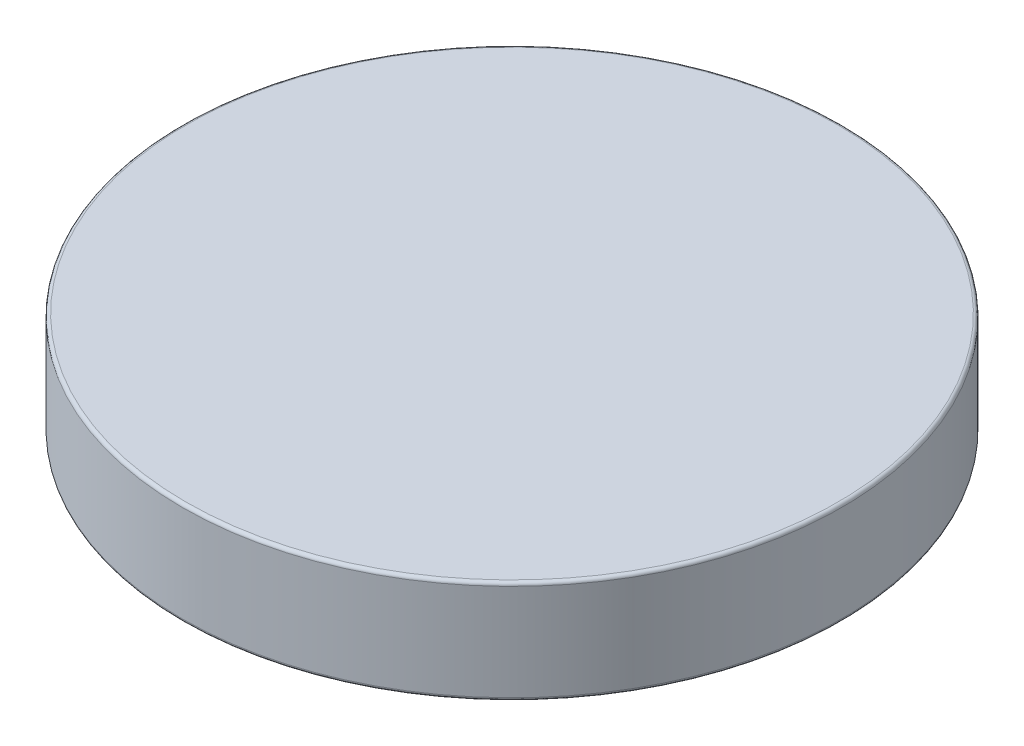
SolidWorks part; units mm, degrees
ref_plane "Front Plane" through (0, 0, 0) normal (0, 0, 1) x (1, 0, 0)
ref_plane "Top Plane" through (0, 0, 0) normal (0, 1, 0) x (1, 0, 0)
ref_plane "Right Plane" through (0, 0, 0) normal (1, 0, 0) x (0, 0, -1)
sketch "Sketch1" plane through (0, 0, 0) normal (0, 1, 0) x (1, 0, 0)
  circle A0 centre (0, 0) radius 2.54
  dimension "D1" = 5.08
extrude "magnet" add sketch "Sketch1" along normal blind 0.7937
fillet "edge_fillet" radius 0.0254 2 edges at (0, 0, 2.54) (0, 0.7937, 2.54)
equation "\"magnet_diameter\"=0.2"
equation "\"magnet_thickness\"=0.03125"
